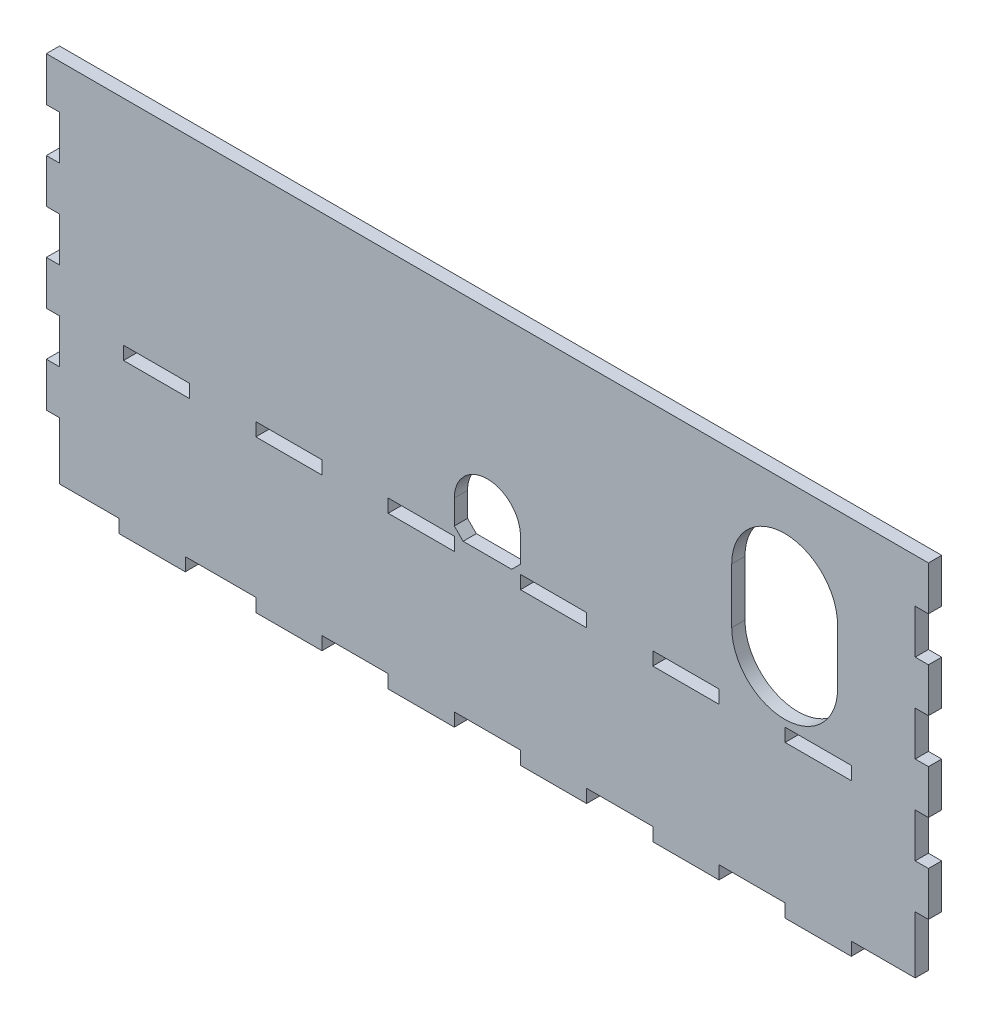
SolidWorks part; units mm, degrees
ref_plane "Front Plane" through (0, 0, 0) normal (0, 0, 1) x (1, 0, 0)
ref_plane "Top Plane" through (0, 0, 0) normal (0, 1, 0) x (1, 0, 0)
ref_plane "Right Plane" through (0, 0, 0) normal (1, 0, 0) x (0, 0, -1)
sketch "Sketch1" plane through (0, 0, 0) normal (0, 0, 1) x (1, 0, 0)
  line L0 (-97, 0) -> (97, 0) construction
  line L1 (0, -25.5) -> (0, 57.5) construction
  line L2 (-97, -12.5) -> (-97, -25.5)
  line L3 (-97, 57.5) -> (97, 57.5)
  line L4 (-100, -12.5) -> (-97, -12.5)
  line L5 (0, -25.5) -> (7.5, -25.5)
  line L6 (-100, -2.5) -> (-100, -12.5)
  line L7 (-97, -2.5) -> (-100, -2.5)
  line L8 (-97, 57.5) -> (-100, 57.5)
  line L9 (-100, 57.5) -> (-100, 47.5)
  line L10 (-100, 47.5) -> (-97, 47.5)
  line L11 (-97, 47.5) -> (-97, 37.5)
  line L12 (-97, 37.5) -> (-100, 37.5)
  line L13 (-100, 37.5) -> (-100, 27.5)
  line L14 (100, 17.5) -> (100, 7.5)
  line L15 (-100, 27.5) -> (-97, 27.5)
  line L16 (-97, 27.5) -> (-97, 17.5)
  line L17 (97, 7.5) -> (100, 7.5)
  line L18 (97, 17.5) -> (100, 17.5)
  line L19 (97, 7.5) -> (97, -2.5)
  line L20 (97, 27.5) -> (97, 17.5)
  line L21 (100, 27.5) -> (97, 27.5)
  line L22 (100, 37.5) -> (100, 27.5)
  line L23 (97, 37.5) -> (100, 37.5)
  line L24 (97, 47.5) -> (97, 37.5)
  line L25 (100, 47.5) -> (97, 47.5)
  line L26 (100, 57.5) -> (100, 47.5)
  line L27 (97, 57.5) -> (100, 57.5)
  line L28 (7.5, -25.5) -> (7.5, -28.5)
  line L29 (7.5, -28.5) -> (22.5, -28.5)
  line L30 (22.5, -28.5) -> (22.5, -25.5)
  line L31 (30, -25.5) -> (37.5, -25.5)
  line L32 (37.5, -25.5) -> (37.5, -28.5)
  line L33 (37.5, -28.5) -> (52.5, -28.5)
  line L34 (52.5, -28.5) -> (52.5, -25.5)
  line L35 (60, -25.5) -> (67.5, -25.5)
  line L36 (67.5, -25.5) -> (67.5, -28.5)
  line L37 (67.5, -28.5) -> (82.5, -28.5)
  line L38 (82.5, -28.5) -> (82.5, -25.5)
  line L39 (22.5, -25.5) -> (30, -25.5)
  line L40 (52.5, -25.5) -> (60, -25.5)
  line L41 (82.5, -25.5) -> (97, -25.5)
  line L42 (0, -25.5) -> (-7.5, -25.5)
  line L43 (-7.5, -25.5) -> (-7.5, -28.5)
  line L44 (-7.5, -28.5) -> (-22.5, -28.5)
  line L45 (-22.5, -28.5) -> (-22.5, -25.5)
  line L46 (-22.5, -25.5) -> (-37.5, -25.5)
  line L47 (-37.5, -25.5) -> (-37.5, -28.5)
  line L48 (-37.5, -28.5) -> (-52.5, -28.5)
  line L49 (-52.5, -28.5) -> (-52.5, -25.5)
  line L50 (-52.5, -25.5) -> (-68.5, -25.5)
  line L51 (-68.5, -25.5) -> (-68.5, -28.5)
  line L52 (97, -2.5) -> (100, -2.5)
  line L53 (100, -2.5) -> (100, -12.5)
  line L54 (100, -12.5) -> (97, -12.5)
  line L55 (97, -12.5) -> (97, -25.5)
  line L56 (-97, 7.5) -> (-97, -2.5)
  line L57 (-97, 17.5) -> (-100, 17.5)
  line L58 (-97, 7.5) -> (-100, 7.5)
  line L59 (-100, 17.5) -> (-100, 7.5)
  line L60 (-68.5, -28.5) -> (-83.5, -28.5)
  line L62 (-83.5, -28.5) -> (-83.5, -25.5)
  line L63 (-83.5, -25.5) -> (-97, -25.5)
  dimension "D2" = 7.5
  dimension "D4" = 83
  dimension "D5" = 10
  dimension "D6" = 194
  dimension "D8" = 7.5
  dimension "D9" = 15
  dimension "D10" = 3
  dimension "D11" = 10
  dimension "D7" = 10
  dimension "D13" = 10
  dimension "D12" = 10
  dimension "D14" = 7.5
  dimension "D15" = 14.5
  dimension "D16" = 10
  dimension "D17" = 10
  dimension "D18" = 3
  dimension "D19" = 15
  dimension "D20" = 15
  dimension "D21" = 15
  dimension "D22" = 16
  dimension "D23" = 15
extrude "Boss-Extrude1" add sketch "Sketch1" along normal blind 3
sketch "Sketch2" plane through (0, 0, 3) normal (0, 0, 1) x (1, 0, 0)
  line L0 (0, -25.5) -> (0, 22.5) construction
  line L1 (-7.5, -25.5) -> (7.5, -25.5) construction
  line L2 (0, 22.5) -> (67.4, 22.5) construction
  line L3 (67.4, 22.5) -> (67.4, 35) construction
  line L4 (55.4, 22.5) -> (55.4, 35)
  line L5 (79.4, 22.5) -> (79.4, 35)
  line L6 (100, 57.5) -> (-100, 57.5) construction
  line L7 (7.5, 6) -> (22.5, 6)
  line L8 (7.5, 6) -> (7.5, 9)
  line L9 (7.5, 9) -> (22.5, 9)
  line L10 (22.5, 6) -> (22.5, 9)
  line L11 (37.5, 6) -> (52.5, 6)
  line L12 (37.5, 6) -> (37.5, 9)
  line L13 (37.5, 9) -> (52.5, 9)
  line L14 (52.5, 6) -> (52.5, 9)
  line L15 (67.5, 6) -> (82.5, 6)
  line L16 (67.5, 6) -> (67.5, 9)
  line L17 (67.5, 9) -> (82.5, 9)
  line L18 (82.5, 6) -> (82.5, 9)
  line L19 (-82.5, 6) -> (-82.5, 9)
  line L20 (-67.5, 9) -> (-82.5, 9)
  line L21 (-67.5, 6) -> (-67.5, 9)
  line L22 (-67.5, 6) -> (-82.5, 6)
  line L23 (-52.5, 6) -> (-52.5, 9)
  line L24 (-37.5, 9) -> (-52.5, 9)
  line L25 (-37.5, 6) -> (-37.5, 9)
  line L26 (-37.5, 6) -> (-52.5, 6)
  line L27 (-22.5, 6) -> (-22.5, 9)
  line L28 (-7.5, 9) -> (-22.5, 9)
  line L29 (-7.5, 6) -> (-7.5, 9)
  line L30 (-7.5, 6) -> (-22.5, 6)
  line L31 (-7.5, 11) -> (-7.5, 16.5)
  line L32 (7.5, 11) -> (7.5, 16.5)
  line L33 (7.5, 11) -> (5.5, 9)
  line L34 (5.5, 9) -> (-5.5, 9)
  line L36 (-7.5, 11) -> (-5.5, 9)
  arc A0 (55.4, 22.5) -> (79.4, 22.5) centre (67.4, 22.5) ccw
  arc A1 (79.4, 35) -> (55.4, 35) centre (67.4, 35) ccw
  arc A2 (7.5, 16.5) -> (-7.5, 16.5) centre (0, 16.5) ccw
  point P6 (67.4, 28.75)
  point P46 (0, 9)
  dimension "D4" = 12
  dimension "D10" = 15
  dimension "D1" = 48
  dimension "D2" = 67.4
  dimension "D3" = 12.5
  dimension "D5" = 7.5
  dimension "D6" = 15
  dimension "D7" = 3
  dimension "D8" = 48.5
  dimension "D9" = 7.5
  dimension "D12" = 2
  dimension "D13" = 2
  dimension "D11" = 3
extrude "Cut-Extrude1" cut sketch "Sketch2" against normal blind 10
